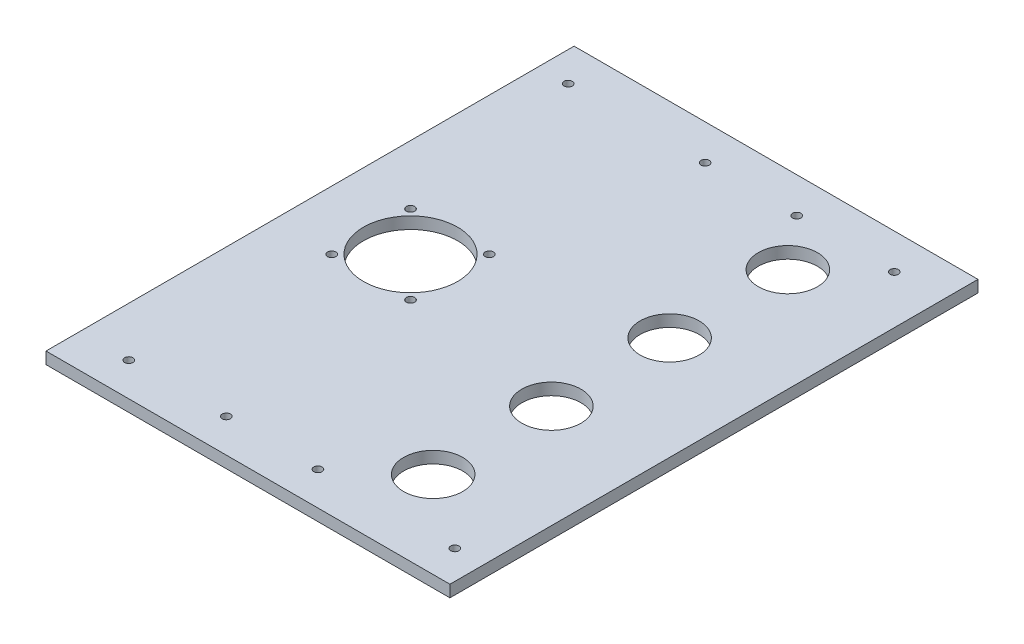
SolidWorks part; units mm, degrees
material "Acrílico (médio-alto impacto)"
ref_plane "Front Plane" through (0, 0, 0) normal (0, 0, 1) x (1, 0, 0)
ref_plane "Top Plane" through (0, 0, 0) normal (0, 1, 0) x (1, 0, 0)
ref_plane "Right Plane" through (0, 0, 0) normal (1, 0, 0) x (0, 0, -1)
sketch "Esboço1" plane through (0, 0, 0) normal (0, -1, 0) x (1, 0, 0)
  line L1 (-102.5, -134) -> (102.5, -134)
  line L2 (-102.5, -134) -> (-102.5, 134)
  line L20 (-102.5, 134) -> (102.5, 134)
  line L21 (102.5, -134) -> (102.5, 134)
  line L22 (-102.5, -134) -> (102.5, 134) construction
  line L23 (-102.5, 134) -> (102.5, -134) construction
  point P0 (0, 0)
  dimension "D1" = 268
  dimension "D2" = 205
extrude "Ressalto-extrusão1" add sketch "Esboço1" against normal blind 6
sketch "Esboço3" plane through (0, 6, 0) normal (0, 1, 0) x (1, 0, 0)
  line L0 (-102.5, -134) -> (-102.5, 134) construction
  line L5 (102.5, -134) -> (-102.5, -134) construction
  circle A0 centre (-52.5, 1) radius 23.9
  circle A1 centre (-72.5, 21) radius 2.1
  circle A2 centre (-32.5, 21) radius 2.1
  circle A3 centre (-32.5, -19) radius 2.1
  circle A4 centre (-72.5, -19) radius 2.1
  point P0 (-52.5, 1)
  dimension "D5" = 20
  dimension "D6" = 20
  dimension "D1" = 20
  dimension "D2" = 47.8
  dimension "D7" = 4.2
  dimension "D3" = 135
  dimension "D4" = 50
  dimension "D8" = 40
extrude "Corte-extrusão4" cut sketch "Esboço3" against normal through all
sketch "Esboço4" plane through (0, 6, 0) normal (0, 1, 0) x (1, 0, 0)
  circle A0 centre (50, 30) radius 15
  circle A1 centre (50, -30) radius 15
  circle A2 centre (50, 90) radius 15
  circle A3 centre (50, -90) radius 15
  dimension "D1" = 30
  dimension "D2" = 30
  dimension "D4" = 50
  dimension "D3" = 60
  dimension "D5" = 60
  dimension "D6" = 60
extrude "Corte-extrusão5" cut sketch "Esboço4" against normal through all
hole_wizard "Furo de diâmetro Ø4.2 (4.2)1" positions "Esboço5" profile "Esboço6" hole size "Ø4.2" standard "ISO" end condition through all
sketch "Esboço5" plane through (0, 6, 0) normal (0, 1, 0) x (1, 0, 0)
  point P0 (-87.5, 116)
  point P3 (-18, 116)
  point P6 (28.5, 116)
  point P9 (78, 116)
  point P12 (-77.5, -117)
  point P15 (-28, -117)
  point P18 (18.5, -117)
  point P21 (88, -117)
sketch "Esboço6" plane through (-87.5, 6, -116) normal (1, 0, 0) x (0, 0, 1)
  line L0 (0, 0) -> (0, 6)
  line L1 (0, 6) -> (2.1, 6)
  line L2 (2.1, 6) -> (2.1, 0)
  line L5 (2.1, 0) -> (0, 0)
  line L11 (0, -6.35) -> (0, 107.95) construction
  dimension "Thru Hole Dia." = 4.2
  dimension "Thru Hole Depth" = 6
